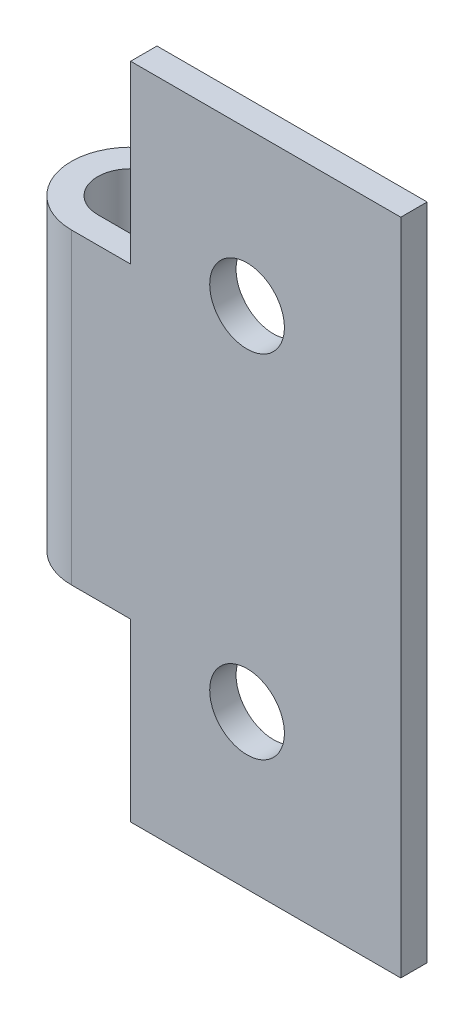
SolidWorks part; units mm, degrees
material "AISI 304"
ref_plane "Ön Düzlem" through (0, 0, 0) normal (0, 0, 1) x (1, 0, 0)
ref_plane "Üst Düzlem" through (0, 0, 0) normal (0, 1, 0) x (1, 0, 0)
ref_plane "Sağ Düzlem" through (0, 0, 0) normal (1, 0, 0) x (0, 0, -1)
sketch "Çizim1" plane through (0, 0, 0) normal (0, 1, 0) x (1, 0, 0)
  line L0 (0, 7.8372) -> (0, -8.9997) construction
  line L1 (0, 0.6) -> (15, 0.6)
  line L3 (0, -0.6) -> (15, -0.6)
  line L4 (15, 0.6) -> (15, -0.6)
  line L5 (0, 0) -> (15, -0.6) construction
  line L6 (0, 0) -> (15, 0.6) construction
  line L7 (2.3018, 0.6888) -> (1.2788, 1.316)
  arc A0 (2.3018, 0.6888) -> (0, -0.6) centre (0, 2.1) ccw
  arc A4 (1.2788, 1.316) -> (0, 0.6) centre (0, 2.1) ccw
  point P0 (0, 0)
  dimension "D1" = 2.7
  dimension "D2" = 1.2
extrude "Yükseklik-Ekstrüzyon1" add sketch "Çizim1" against normal blind 30
sketch "Çizim3" plane through (0, -30, 0) normal (0, -1, 0) x (1, 0, 0)
  line L0 (1.2788, -1.316) -> (2.3018, -0.6888) construction
  line L1 (1.2788, -1.316) -> (2.3018, -0.6888)
  line L3 (0, -0.6) -> (2.7, -0.6)
  line L4 (2.7, -0.6) -> (2.7, 0.6)
  line L5 (0, 0.6) -> (15, 0.6) construction
  line L6 (15, -0.6) -> (0, -0.6) construction
  line L7 (0, 0.6) -> (2.7, 0.6)
  arc A0 (0, -0.6) -> (1.2788, -1.316) centre (0, -2.1) ccw construction
  arc A1 (0, 0.6) -> (2.3018, -0.6888) centre (0, -2.1) ccw construction
  arc A2 (0, -0.6) -> (1.2788, -1.316) centre (0, -2.1) ccw
  arc A3 (0, 0.6) -> (2.3018, -0.6888) centre (0, -2.1) ccw
extrude "Kes-Ekstrüzyon2" cut sketch "Çizim3" against normal blind 8
sketch "Çizim4" plane through (0, 0, -0.6) normal (0, 0, -1) x (-1, 0, 0)
  line L0 (0, -31.2224) -> (0, 1.1804) construction
  line L2 (-15, 0) -> (0, 0) construction
  circle A0 centre (-8, -23) radius 1.7
  circle A1 centre (-8, -7) radius 1.7
  dimension "D4" = 3.4
  dimension "D5" = 3.4
  dimension "D1" = 8
  dimension "D2" = 16
  dimension "D3" = 7
extrude "Kes-Ekstrüzyon3" cut sketch "Çizim4" against normal blind 1.2
ref_plane "Düzlem1" through (0, -15, 0) normal (0, -1, 0) x (-1, 0, 0)
mirror "Aynalama1" about plane through (0, -15, 0) normal (0, -1, 0) of "Kes-Ekstrüzyon2"
